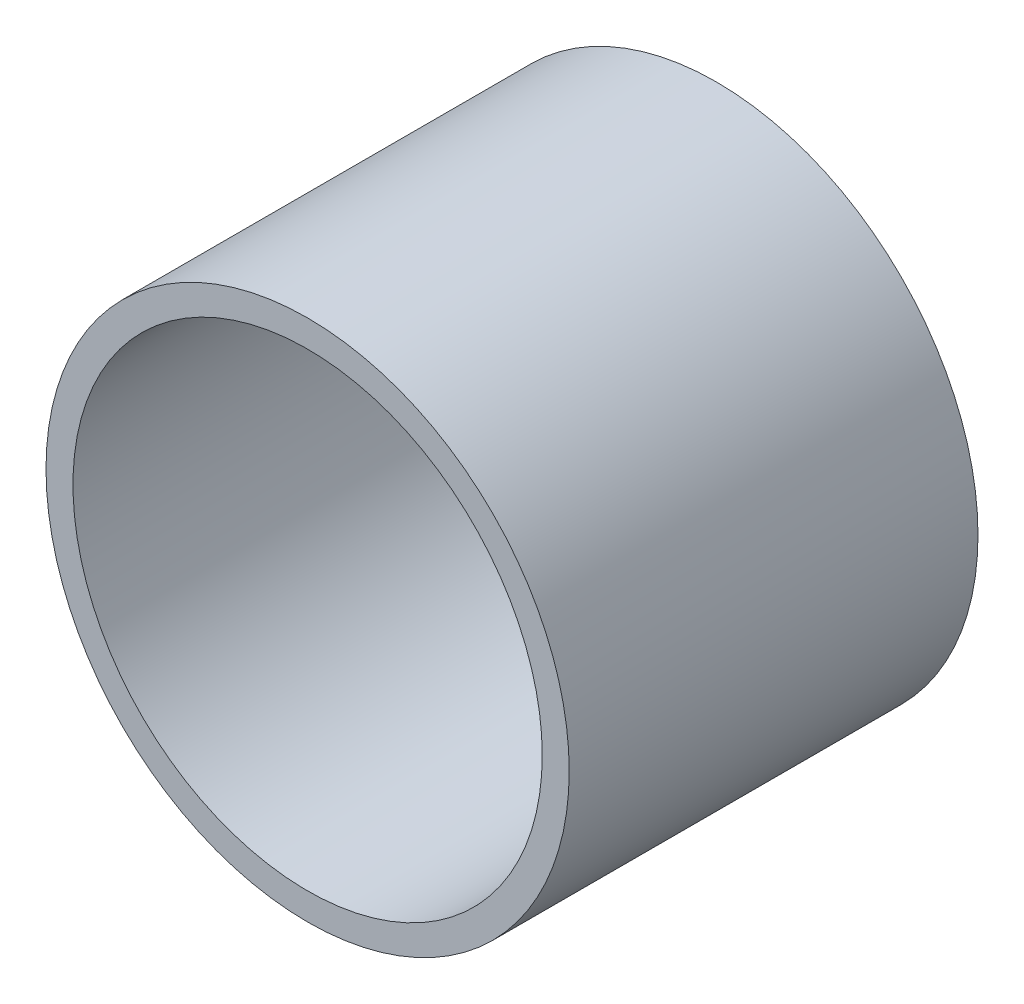
SolidWorks part; units mm, degrees
ref_plane "Front Plane" through (0, 0, 0) normal (0, 0, 1) x (1, 0, 0)
ref_plane "Top Plane" through (0, 0, 0) normal (0, 1, 0) x (1, 0, 0)
ref_plane "Right Plane" through (0, 0, 0) normal (1, 0, 0) x (0, 0, -1)
sketch "Sketch1" plane through (0, 0, 0) normal (0, 0, 1) x (1, 0, 0)
  circle A0 centre (0, 0) radius 32
  circle A1 centre (0, 0) radius 28.7
  dimension "D1" = 64
  dimension "D2" = 57.4
extrude "Boss-Extrude1" add sketch "Sketch1" along normal blind 50
